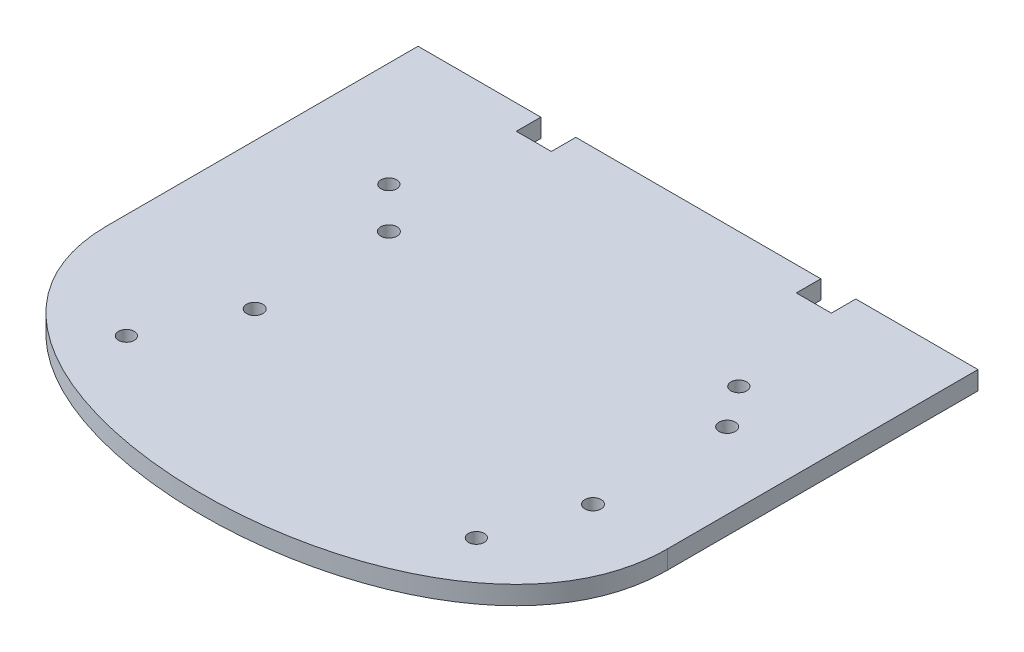
SolidWorks part; units mm, degrees
ref_plane "Front Plane" through (0, 0, 0) normal (0, 0, 1) x (1, 0, 0)
ref_plane "Top Plane" through (0, 0, 0) normal (0, 1, 0) x (1, 0, 0)
ref_plane "Right Plane" through (0, 0, 0) normal (1, 0, 0) x (0, 0, -1)
sketch "Sketch2" plane through (0, 0, 0) normal (0, 1, 0) x (1, 0, 0)
  line L4 (-48, -33.6908) -> (-48, 91.0268) construction
  line L5 (48, -42.5) -> (-48, -42.5) construction
  line L6 (48, -42.5) -> (48, 42.5) construction
  line L7 (48, 42.5) -> (-48, 42.5)
  line L8 (-48, -42.5) -> (-48, 42.5) construction
  line L9 (48, -42.5) -> (-48, 42.5) construction
  line L10 (48, 42.5) -> (-48, -42.5) construction
  line L11 (48, 148.5724) -> (48, -105.4276) construction
  line L12 (-48, 42.5) -> (-48, -10.75)
  line L13 (48, 42.5) -> (48, -10.75)
  spline S0 degree 3 poles (-48, -10.75) (-48, -53.0833) (48, -53.0833) (48, -10.75) knots 0 0 0 0 1 1 1 1
  point P0 (0, 0)
  dimension "D3" = 180
  dimension "D4" = 127
  dimension "D5" = 85
  dimension "D1" = 96
  dimension "D2" = 180
  dimension "D6" = 127
extrude "Boss-Extrude1" add sketch "Sketch2" along normal blind 3.175
sketch "Sketch3" plane through (0, 3.175, 0) normal (0, 1, 0) x (1, 0, 0)
  line L0 (0, 0) -> (0, 43.6246) construction
  line L9 (-48, 42.5) -> (-48, -10.75) construction
  line L10 (48, 42.5) -> (-48, 42.5) construction
  line L11 (-23, 12.5) -> (-23, -10.5) construction
  line L12 (35, 12.5) -> (35, -10.5) construction
  line L13 (-30, 19.5) -> (-30, -25.5) construction
  line L14 (30, 19.5) -> (30, -25.5) construction
  line L15 (0, -42.5) -> (29.21, -42.5) construction
  circle A2 centre (-30, 19.5) radius 1.35
  circle A5 centre (-30, -25.5) radius 1.35
  circle A6 centre (30, -25.5) radius 1.35
  circle A7 centre (30, 19.5) radius 1.35
  circle A10 centre (-23, 12.5) radius 1.397
  circle A11 centre (-23, -10.5) radius 1.397
  circle A12 centre (35, -10.5) radius 1.397
  circle A13 centre (35, 12.5) radius 1.397
  spline S0 degree 3 poles (-48, -10.75) (-48, -53.0833) (48, -53.0833) (48, -10.75) knots 0 0 0 0 1 1 1 1 construction
  dimension "D5" = 30
  dimension "D6" = 58
  dimension "D9" = 2.7
  dimension "D2" = 2.794
  dimension "D7" = 25
  dimension "D3" = 23
  dimension "D4" = 58
  dimension "D10" = 23
  dimension "D11" = 30
  dimension "D12" = 45
extrude "Cut-Extrude1" cut sketch "Sketch3" against normal through all and the other way through all
sketch "Sketch5" plane through (0, 3.175, 0) normal (0, 1, 0) x (1, 0, 0)
  line L0 (0.0511, -12) -> (0.0511, 44.8666) construction
  line L10 (27.0511, 42.5) -> (27.0511, 38.3)
  line L11 (21.0511, 42.5) -> (27.0511, 42.5)
  line L12 (21.0511, 38.3) -> (27.0511, 38.3)
  line L13 (21.0511, 42.5) -> (21.0511, 38.3)
  line L18 (-20.9489, 42.5) -> (-20.9489, 38.3)
  line L19 (-26.9489, 42.5) -> (-20.9489, 42.5)
  line L20 (-26.9489, 38.3) -> (-20.9489, 38.3)
  line L21 (-26.9489, 42.5) -> (-26.9489, 38.3)
  point P2 (-20.9489, 40.4)
  point P3 (0, 0)
  dimension "D1" = 6
  dimension "D2" = 6
extrude "Cut-Extrude2" cut sketch "Sketch5" against normal through all
